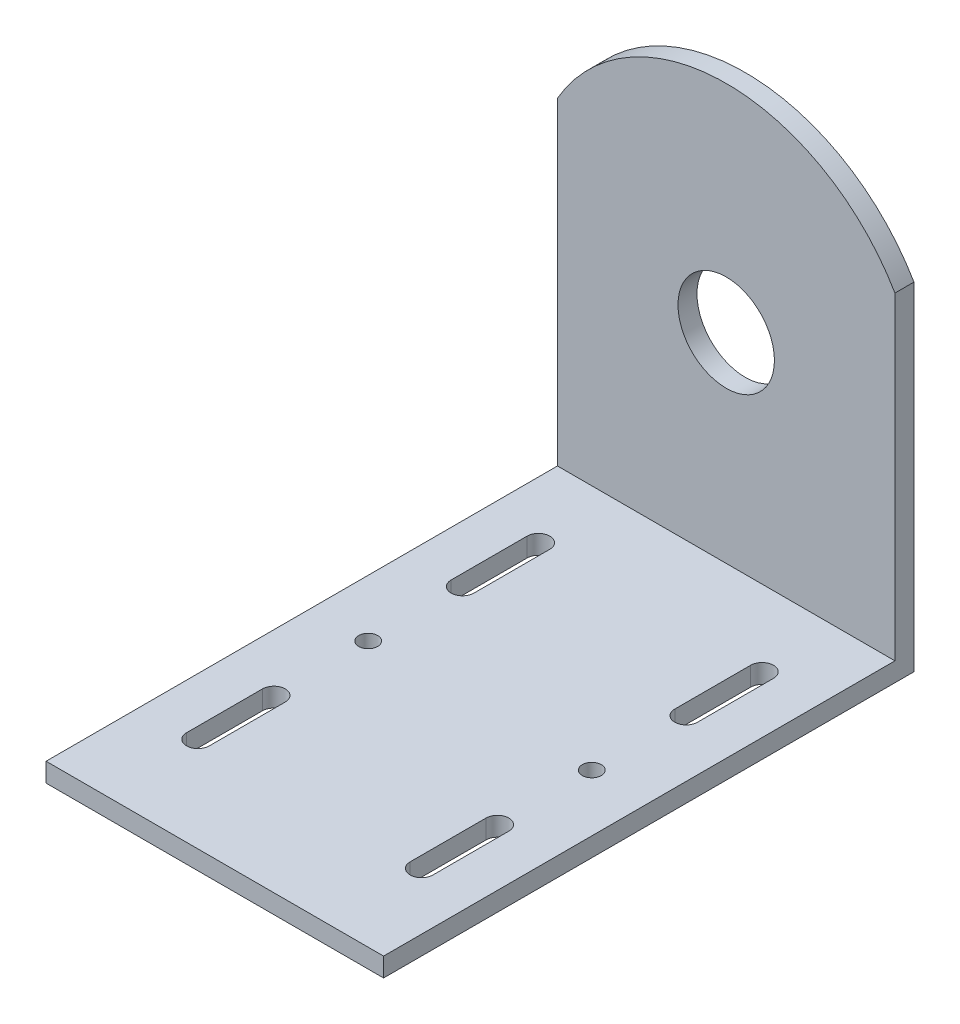
SolidWorks part; units mm, degrees
ref_plane "Front Plane" through (0, 0, 0) normal (0, 0, 1) x (1, 0, 0)
ref_plane "Top Plane" through (0, 0, 0) normal (0, 1, 0) x (1, 0, 0)
ref_plane "Right Plane" through (0, 0, 0) normal (1, 0, 0) x (0, 0, -1)
sketch "Sketch1" plane through (0, 0, 0) normal (0, 0, 1) x (1, 0, 0)
  line L0 (-88.9, 0) -> (88.9, 0)
  line L1 (0, 0) -> (0, 228.6) construction
  line L2 (-88.9, 0) -> (-88.9, 177.797) construction
  line L3 (88.9, 0) -> (88.9, 177.797) construction
  line L4 (-88.9, 177.797) -> (-88.9, 0)
  line L5 (88.9, 177.797) -> (88.9, 0)
  arc A0 (88.9, 177.797) -> (-88.9, 177.797) centre (0, 126.238) ccw
  point P4 (0, 0)
  point P9 (0, 126.238)
  dimension "D1" = 177.8
  dimension "D2" = 228.6
  dimension "D3" = 102.362
sketch3d "3DSketch1"
  line L0 (0, 0, 0) -> (0, 0, 279.4) construction
  line L1 (88.9, 0, 0) -> (88.9, 0, 279.4)
  line L2 (-88.9, 0, 0) -> (-88.9, 0, 279.4)
  line L3 (-88.9, 0, 279.4) -> (88.9, 0, 279.4)
  line L4 (-88.9, 0, 0) -> (88.9, 0, 0)
  dimension "D1" = 279.4
extrude "Boss-Extrude2" add sketch "3DSketch1" along direction (0, 1, 0) on the side of the normal blind 10
extrude "Boss-Extrude3" add sketch "Sketch1" along normal blind 10
sketch "Sketch2" plane through (0, 0, 0) normal (0, 0, -1) x (-1, 0, 0)
  line L0 (0, 0) -> (0, 229.0074) construction
  line L1 (-88.9, 115.3) -> (88.9, 115.3)
  line L2 (88.9, 0) -> (88.9, 177.797) construction
  line L3 (88.9, 0) -> (-88.9, 0) construction
  line L4 (0, 115.3) -> (43.8812, 156.2199) construction
  line L5 (0, 115.3) -> (-38.1838, 153.4838) construction
  line L6 (0, 115.3) -> (64.305, 55.961) construction
  line L7 (0, 115.3) -> (-54.1634, 43.4228) construction
  arc A0 (88.9, 177.797) -> (-88.9, 177.797) centre (0, 126.238) ccw construction
  circle A1 centre (0, 115.3) radius 25.4
  circle A2 centre (0, 115.3) radius 10
  point P11 (0, 115.3)
  dimension "D2" = 50.8
  dimension "D3" = 20
  dimension "D1" = 115.3
  dimension "D4" = 45
  dimension "D5" = 54
  dimension "D7" = 43
  dimension "D8" = 60
  dimension "D9" = 42.7
  dimension "D10" = 87.5
  dimension "D12" = 127
  dimension "D13" = 90
extrude "Cut-Extrude2" cut sketch "Sketch2" against normal through all
sketch "Sketch3" plane through (0, 10, 0) normal (0, 1, 0) x (1, 0, 0)
  line L0 (-58.9, -10) -> (-58.9, -279.4) construction
  line L1 (-88.9, -10) -> (88.9, -10) construction
  line L2 (88.9, -279.4) -> (-88.9, -279.4) construction
  line L3 (0, 0) -> (0, -279.4) construction
  line L4 (-88.9, -279.4) -> (-88.9, -10) construction
  line L5 (-58.9, -90) -> (-58.9, -50) construction
  line L6 (-64.9, -90) -> (-64.9, -50)
  line L7 (-52.9, -90) -> (-52.9, -50)
  line L8 (0, -139.7) -> (-88.9, -139.7) construction
  line L9 (58.9, -90) -> (58.9, -50) construction
  line L10 (64.9, -90) -> (64.9, -50)
  line L11 (52.9, -90) -> (52.9, -50)
  line L12 (0, -139.7) -> (88.9, -139.7) construction
  line L13 (88.9, -10) -> (88.9, -279.4) construction
  line L14 (58.9, -189.4) -> (58.9, -229.4) construction
  line L15 (64.9, -189.4) -> (64.9, -229.4)
  line L16 (52.9, -189.4) -> (52.9, -229.4)
  line L17 (-58.9, -189.4) -> (-58.9, -229.4) construction
  line L18 (-64.9, -189.4) -> (-64.9, -229.4)
  line L19 (-52.9, -189.4) -> (-52.9, -229.4)
  arc A0 (-64.9, -90) -> (-52.9, -90) centre (-58.9, -90) ccw
  arc A1 (-52.9, -50) -> (-64.9, -50) centre (-58.9, -50) ccw
  arc A2 (64.9, -90) -> (52.9, -90) centre (58.9, -90) cw
  arc A3 (52.9, -50) -> (64.9, -50) centre (58.9, -50) cw
  arc A4 (64.9, -189.4) -> (52.9, -189.4) centre (58.9, -189.4) ccw
  arc A5 (52.9, -229.4) -> (64.9, -229.4) centre (58.9, -229.4) ccw
  arc A6 (-64.9, -189.4) -> (-52.9, -189.4) centre (-58.9, -189.4) cw
  arc A7 (-52.9, -229.4) -> (-64.9, -229.4) centre (-58.9, -229.4) cw
  point P11 (-58.9, -70)
  point P14 (-58.9, -70)
  point P23 (58.9, -70)
  point P33 (58.9, -209.4)
  point P40 (-58.9, -209.4)
  dimension "D1" = 30
  dimension "D2" = 60
  dimension "D3" = 40
  dimension "D4" = 12
extrude "Cut-Extrude5" cut sketch "Sketch3" against normal blind 10
sketch "Sketch4" plane through (0, 10, 0) normal (0, 1, 0) x (1, 0, 0)
  line L0 (0, 0) -> (0, -279.4) construction
  line L1 (88.9, -279.4) -> (-88.9, -279.4) construction
  line L2 (-88.9, -139.7) -> (88.9, -139.7)
  line L3 (88.9, -10) -> (88.9, -279.4) construction
  line L4 (-58.9, -96) -> (-58.9, -183.4) construction
  arc A1 (-64.9, -90) -> (-52.9, -90) centre (-58.9, -90) ccw construction
  arc A2 (-52.9, -189.4) -> (-64.9, -189.4) centre (-58.9, -189.4) ccw construction
  circle A3 centre (-58.9, -139.7) radius 5
  circle A4 centre (58.9, -139.7) radius 5
  point P11 (0, -139.7)
extrude "Cut-Extrude6" cut sketch "Sketch4" against normal through all contours A3 | A4
sketch "Sketch5" plane through (0, 0, 0) normal (0, 0, -1) x (-1, 0, 0)
  line L0 (0, 0) -> (0, 115.3) construction
